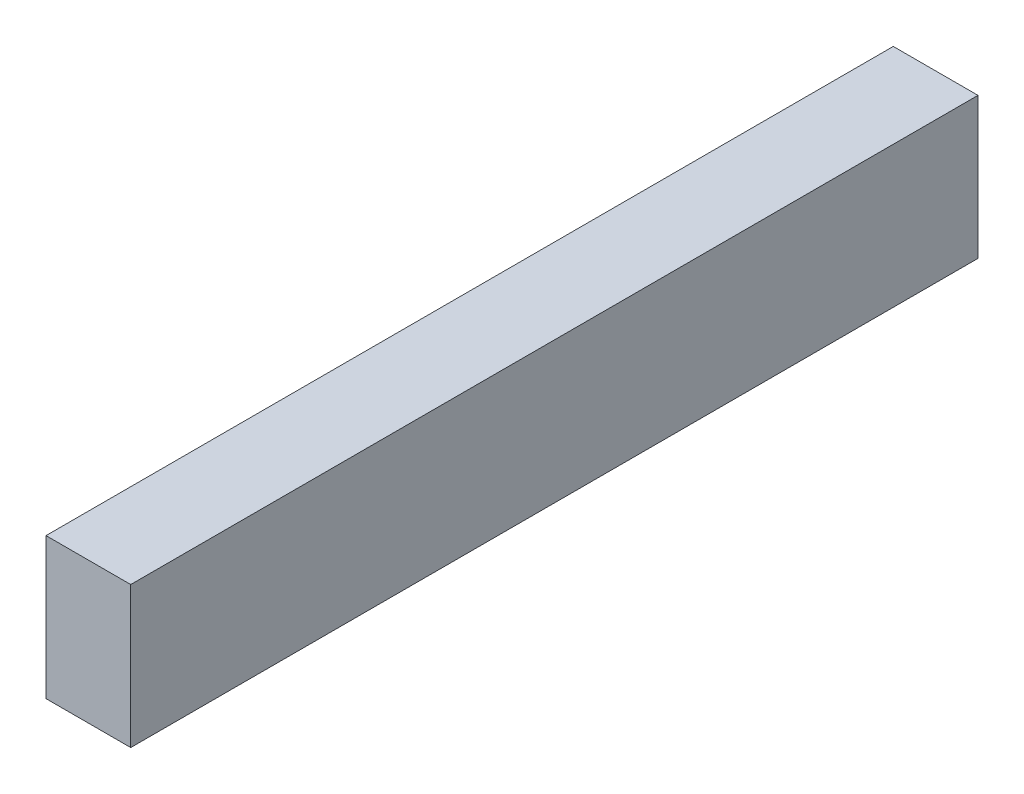
SolidWorks part; units mm, degrees
ref_plane "前视基准面" through (0, 0, 0) normal (0, 0, 1) x (1, 0, 0)
ref_plane "上视基准面" through (0, 0, 0) normal (0, 1, 0) x (1, 0, 0)
ref_plane "右视基准面" through (0, 0, 0) normal (1, 0, 0) x (0, 0, -1)
sketch "草图1" plane through (0, 0, 0) normal (0, 0, 1) x (1, 0, 0)
  line L1 (-15, 25) -> (15, 25)
  line L2 (-15, 25) -> (-15, -25)
  line L3 (-15, -25) -> (15, -25)
  line L4 (15, 25) -> (15, -25)
  line L5 (-15, 25) -> (15, -25) construction
  line L6 (-15, -25) -> (15, 25) construction
  point P0 (0, 0)
  dimension "D1" = 30
  dimension "D2" = 50
extrude "凸台-拉伸1" add sketch "草图1" along normal blind 300
